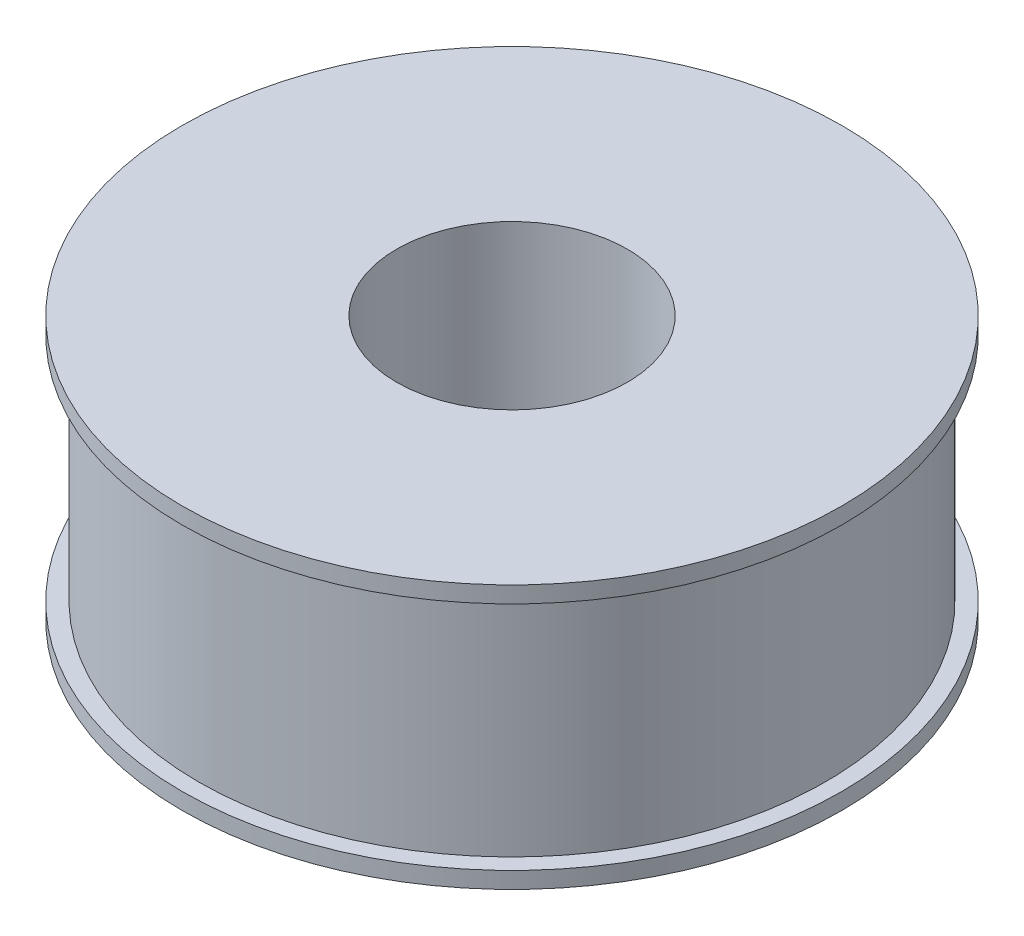
SolidWorks part; units mm, degrees
ref_plane "Front Plane" through (0, 0, 0) normal (0, 0, 1) x (1, 0, 0)
ref_plane "Top Plane" through (0, 0, 0) normal (0, 1, 0) x (1, 0, 0)
ref_plane "Right Plane" through (0, 0, 0) normal (1, 0, 0) x (0, 0, -1)
sketch "Sketch2" plane through (0, 0, 0) normal (0, 1, 0) x (1, 0, 0)
  circle A0 centre (0, 0) radius 10
  circle A1 centre (0, 0) radius 3.5
  dimension "D1" = 20
  dimension "D2" = 7
extrude "Boss-Extrude1" add sketch "Sketch2" along normal blind 8
sketch "Sketch3" plane through (0, 0, 0) normal (0, 0, 1) x (1, 0, 0)
  line L0 (-10, 8) -> (-10, 0) construction
  line L1 (-10.5, 0.5) -> (-9.5, 0.5)
  line L2 (-10.5, 0.5) -> (-10.5, 7.5)
  line L3 (-10.5, 7.5) -> (-9.5, 7.5)
  line L4 (-9.5, 0.5) -> (-9.5, 7.5)
  line L5 (-10.5, 0.5) -> (-9.5, 7.5) construction
  line L6 (-10.5, 7.5) -> (-9.5, 0.5) construction
  line L7 (10, 8) -> (-10, 8) construction
  line L8 (0, 8) -> (0, 0) construction
  point P0 (-10, 4)
  dimension "D1" = 0.5
  dimension "D2" = 1
revolve "Cut-Revolve1" cut sketch "Sketch3" angle 360 about L8
